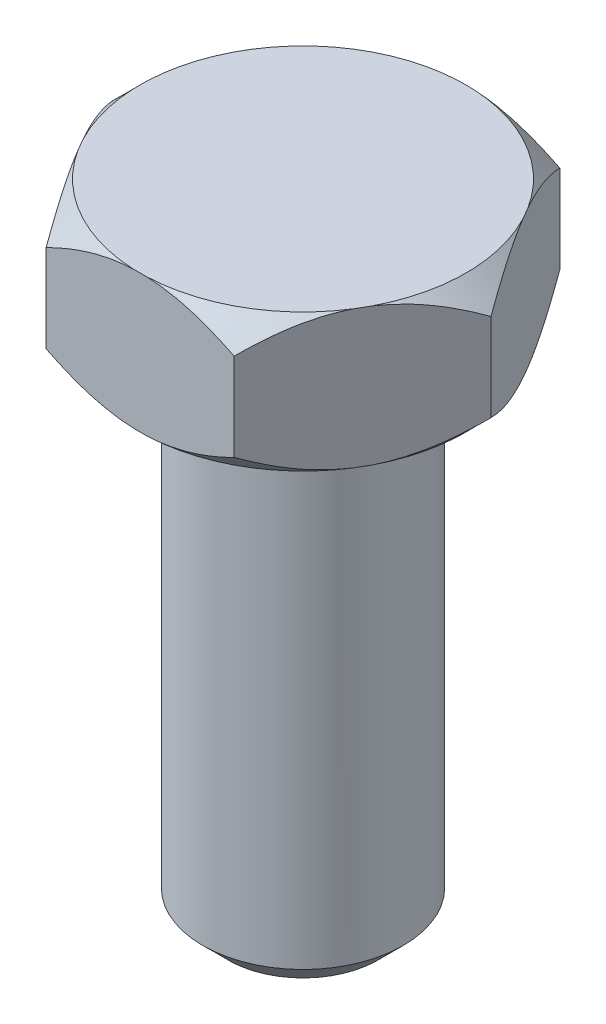
SolidWorks part; units mm, degrees
ref_plane "Спереди" through (0, 0, 0) normal (0, 0, 1) x (1, 0, 0)
ref_plane "Сверху" through (0, 0, 0) normal (0, 1, 0) x (1, 0, 0)
ref_plane "Справа" through (0, 0, 0) normal (1, 0, 0) x (0, 0, -1)
sketch "Эскиз1" plane through (0, 0, 0) normal (0, 1, 0) x (1, 0, 0)
  line L0 (-3.7528, 6.5) -> (3.7528, 6.5)
  line L1 (3.7528, 6.5) -> (7.5056, 0)
  line L2 (7.5056, 0) -> (3.7528, -6.5)
  line L3 (3.7528, -6.5) -> (-3.7528, -6.5)
  line L4 (-3.7528, -6.5) -> (-7.5056, 0)
  line L5 (-7.5056, 0) -> (-3.7528, 6.5)
  dimension "D5" = 6.5
  dimension "D2" = 120
  dimension "D3" = 120
  dimension "D4" = 120
  dimension "D6" = 6.5
  dimension "D7" = 6.5
  dimension "D8" = 6.5
  dimension "D9" = 6.5
  dimension "D10" = 120
  dimension "D11" = 6.5
extrude "Вытянуть1" add sketch "Эскиз1" against normal blind 5.5
sketch "Эскиз5" plane through (0, -5.5, 0) normal (0, -1, 0) x (1, 0, 0)
  circle A0 centre (0, 0) radius 4
  dimension "D1" = 8
extrude "Вытянуть2" add sketch "Эскиз5" along normal blind 20
chamfer "Фаска1" distance 1 angle 45 1 edges at (0, -25.5, -4)
ref_axis "Ось1" through (0, -5.5, 0) along (0, -1, 0)
ref_plane "Плоскость1" through (0, 0, 0) normal (0, 0, 1) x (1, 0, 0)
sketch "Эскиз4" plane through (0, 0, 0) normal (0, 0, 1) x (1, 0, 0)
  line L0 (-7.5056, -1) -> (-6.5056, 0)
  line L1 (-7.5056, -5.5) -> (-7.5056, 0) construction
  line L2 (-7.5056, 0) -> (-3.7528, 0) construction
  line L3 (-6.5056, 0) -> (-7.5056, 0)
  line L4 (-7.5056, 0) -> (-7.5056, -1)
  line L5 (-7.5056, -4.5) -> (-6.5056, -5.5)
  line L6 (-7.5056, -5.5) -> (-3.7528, -5.5) construction
  line L7 (-6.5056, -5.5) -> (-7.5056, -5.5)
  line L8 (-7.5056, -5.5) -> (-7.5056, -4.5)
  dimension "D1" = 1
  dimension "D2" = 1
  dimension "D3" = 1
  dimension "D4" = 1
revolve "Вырез-Повернуть1" cut sketch "Эскиз4" angle 360 about axis through (0, -5.5, 0) along (0, -1, 0)
